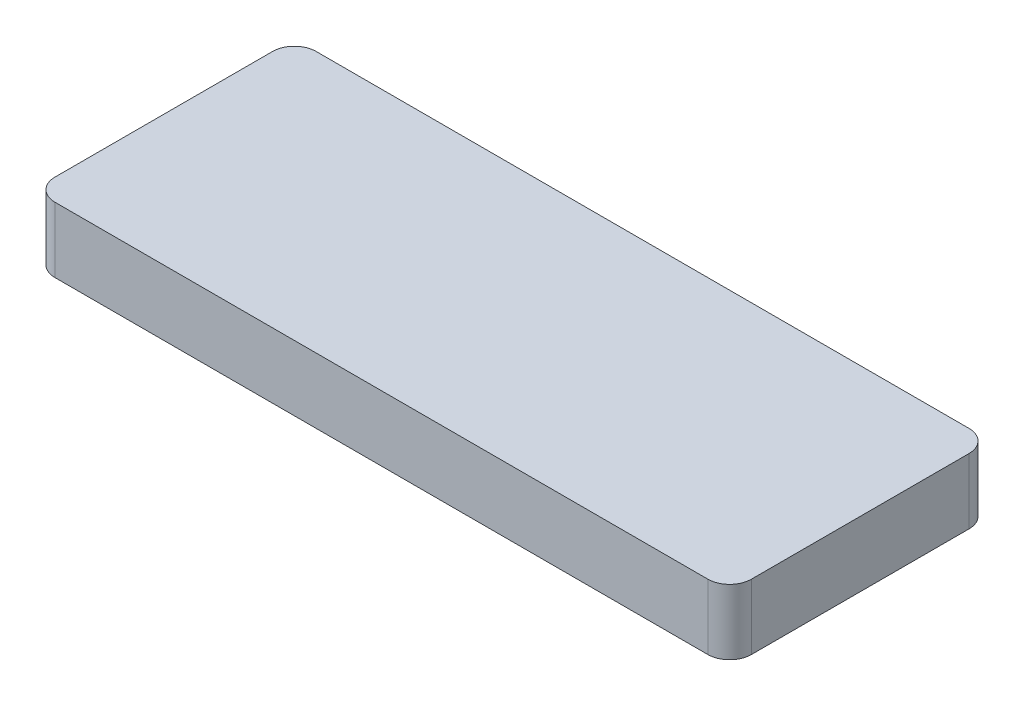
SolidWorks part; units mm, degrees
ref_plane "Front" through (0, 0, 0) normal (0, 0, 1) x (1, 0, 0)
ref_plane "Top" through (0, 0, 0) normal (0, 1, 0) x (1, 0, 0)
ref_plane "Right" through (0, 0, 0) normal (1, 0, 0) x (0, 0, -1)
sketch "Sketch1" plane through (0, 0, 0) normal (0, 1, 0) x (1, 0, 0)
  line L1 (-95.25, -38.1) -> (95.25, -38.1)
  line L2 (-101.6, -31.75) -> (-101.6, 31.75)
  line L3 (-95.25, 38.1) -> (95.25, 38.1)
  line L4 (101.6, -31.75) -> (101.6, 31.75)
  line L5 (-101.6, -38.1) -> (101.6, 38.1) construction
  line L6 (-101.6, 38.1) -> (101.6, -38.1) construction
  arc A0 (95.25, -38.1) -> (101.6, -31.75) centre (95.25, -31.75) ccw
  arc A1 (-101.6, 31.75) -> (-95.25, 38.1) centre (-95.25, 31.75) cw
  arc A2 (-95.25, -38.1) -> (-101.6, -31.75) centre (-95.25, -31.75) cw
  arc A3 (95.25, 38.1) -> (101.6, 31.75) centre (95.25, 31.75) cw
  point P0 (0, 0)
  dimension "D3" = 6.35
  dimension "D1" = 203.2
  dimension "D2" = 76.2
extrude "Boss-Extrude1" add sketch "Sketch1" along normal blind 19.05
